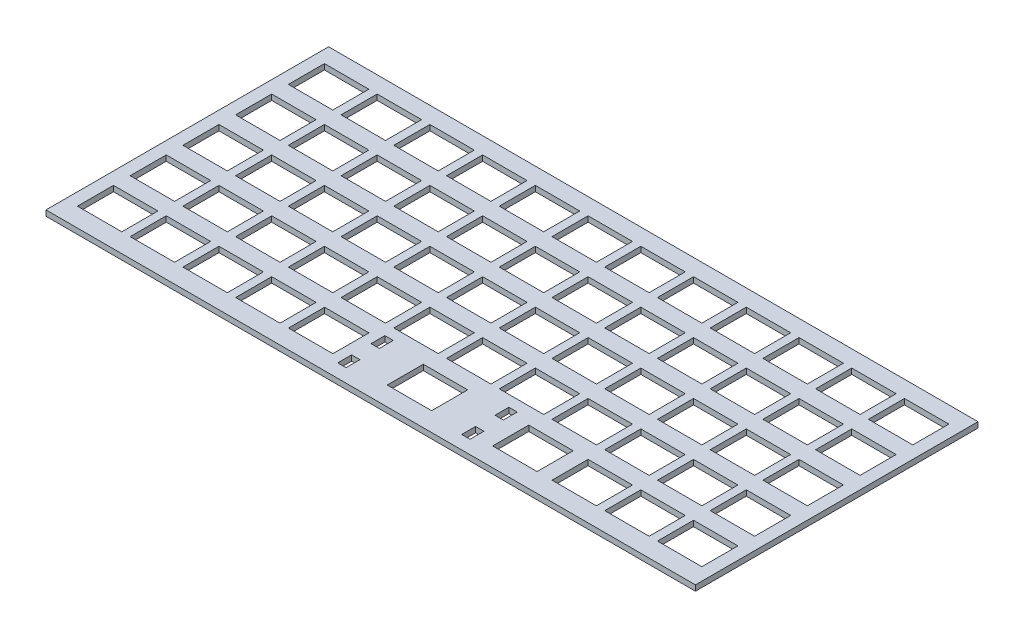
SolidWorks part; units mm, degrees
material "6061-T6 (SS)"
ref_plane "Front Plane" through (0, 0, 0) normal (0, 0, 1) x (1, 0, 0)
ref_plane "Top Plane" through (0, 0, 0) normal (0, 1, 0) x (1, 0, 0)
ref_plane "Right Plane" through (0, 0, 0) normal (1, 0, 0) x (0, 0, -1)
sketch "Sketch1" plane through (0, 0, 0) normal (0, 1, 0) x (1, 0, 0)
  line L0 (-77.1086, 41.2457) -> (-96.1086, 41.2457) construction
  line L1 (-96.1086, 41.2457) -> (-115.1086, 41.2457) construction
  line L2 (-115.1086, -53.7543) -> (-96.1086, -53.7543) construction
  line L3 (-96.1086, -53.7543) -> (-77.1086, -53.7543) construction
  line L4 (-96.1086, 22.2457) -> (-96.1086, 3.2457) construction
  line L5 (-96.1086, -15.7543) -> (-96.1086, -34.7543) construction
  line L6 (93.8914, 41.2457) -> (112.8914, 41.2457) construction
  line L7 (-115.1086, 41.2457) -> (-115.1086, 22.2457) construction
  line L8 (-77.1086, -53.7543) -> (-58.1086, -53.7543) construction
  line L9 (-58.1086, -53.7543) -> (-39.1086, -53.7543) construction
  line L10 (112.8914, 22.2457) -> (112.8914, 3.2457) construction
  line L11 (112.8914, 22.2457) -> (93.8914, 22.2457) construction
  line L12 (-77.1086, -15.7543) -> (-77.1086, 3.2457) construction
  line L13 (93.8914, 22.2457) -> (74.8914, 22.2457) construction
  line L14 (93.8914, -15.7543) -> (93.8914, 3.2457) construction
  line L15 (74.8914, 22.2457) -> (55.8914, 22.2457) construction
  line L16 (-96.1086, 22.2457) -> (-96.1086, 41.2457) construction
  line L17 (-96.1086, 22.2457) -> (-115.1086, 22.2457) construction
  line L18 (112.8914, 22.2457) -> (112.8914, 41.2457) construction
  line L19 (-39.1086, -53.7543) -> (-20.1086, -53.7543) construction
  line L20 (-20.1086, -53.7543) -> (-1.1086, -53.7543) construction
  line L21 (-77.1086, -15.7543) -> (-77.1086, -34.7543) construction
  line L22 (-77.1086, 3.2457) -> (-77.1086, 22.2457) construction
  line L23 (-77.1086, 3.2457) -> (-96.1086, 3.2457) construction
  line L24 (-96.1086, 3.2457) -> (-115.1086, 3.2457) construction
  line L25 (-77.1086, 22.2457) -> (-77.1086, 41.2457) construction
  line L26 (93.8914, 3.2457) -> (93.8914, 22.2457) construction
  line L27 (93.8914, 22.2457) -> (93.8914, 41.2457) construction
  line L28 (-77.1086, -15.7543) -> (-96.1086, -15.7543) construction
  line L29 (-96.1086, -15.7543) -> (-115.1086, -15.7543) construction
  line L30 (93.8914, 3.2457) -> (112.8914, 3.2457) construction
  line L31 (-1.1086, -53.7543) -> (17.8914, -53.7543) construction
  line L32 (-96.1086, -34.7543) -> (-115.1086, -34.7543) construction
  line L33 (-96.1086, -34.7543) -> (-96.1086, -53.7543) construction
  line L34 (-77.1086, -34.7543) -> (-77.1086, -53.7543) construction
  line L35 (93.8914, -15.7543) -> (93.8914, -34.7543) construction
  line L36 (93.8914, -34.7543) -> (93.8914, -53.7543) construction
  line L37 (93.8914, -15.7543) -> (112.8914, -15.7543) construction
  line L38 (17.8914, -53.7543) -> (36.8914, -53.7543) construction
  line L39 (112.8914, -34.7543) -> (112.8914, -53.7543) construction
  line L40 (-77.1086, 41.2457) -> (-58.1086, 41.2457) construction
  line L41 (-58.1086, 41.2457) -> (-58.1086, 22.2457) construction
  line L42 (-58.1086, 41.2457) -> (-39.1086, 41.2457) construction
  line L43 (-39.1086, 41.2457) -> (-20.1086, 41.2457) construction
  line L44 (-20.1086, 41.2457) -> (-1.1086, 41.2457) construction
  line L45 (-1.1086, 41.2457) -> (17.8914, 41.2457) construction
  line L46 (17.8914, 41.2457) -> (36.8914, 41.2457) construction
  line L47 (-39.1086, 41.2457) -> (-39.1086, 22.2457) construction
  line L48 (-39.1086, 22.2457) -> (-39.1086, 3.2457) construction
  line L49 (-39.1086, -15.7543) -> (-39.1086, 3.2457) construction
  line L50 (-39.1086, -15.7543) -> (-39.1086, -34.7543) construction
  line L51 (-39.1086, -34.7543) -> (-39.1086, -53.7543) construction
  line L52 (36.8914, 41.2457) -> (55.8914, 41.2457) construction
  line L53 (55.8914, 41.2457) -> (74.8914, 41.2457) construction
  line L54 (93.8914, 41.2457) -> (74.8914, 41.2457) construction
  line L55 (-20.1086, -53.7543) -> (-20.1086, -34.7543) construction
  line L56 (-20.1086, -15.7543) -> (-20.1086, -34.7543) construction
  line L57 (-115.1086, 3.2457) -> (-115.1086, 22.2457) construction
  line L58 (-115.1086, -53.7543) -> (-115.1086, -34.7543) construction
  line L59 (-115.1086, -34.7543) -> (-115.1086, -15.7543) construction
  line L60 (-96.1086, -15.7543) -> (-96.1086, 3.2457) construction
  line L61 (-115.1086, -15.7543) -> (-115.1086, 3.2457) construction
  line L62 (-115.1086, -53.7543) -> (-96.1086, -34.7543) construction
  line L63 (36.8914, -53.7543) -> (55.8914, -53.7543) construction
  line L64 (55.8914, -53.7543) -> (74.8914, -53.7543) construction
  line L65 (74.8914, -53.7543) -> (93.8914, -53.7543) construction
  line L66 (93.8914, -53.7543) -> (112.8914, -53.7543) construction
  line L67 (112.8914, 3.2457) -> (112.8914, -15.7543) construction
  line L68 (112.8914, -15.7543) -> (112.8914, -34.7543) construction
  line L69 (-58.1086, 22.2457) -> (-58.1086, 3.2457) construction
  line L70 (-58.1086, 3.2457) -> (-58.1086, -15.7543) construction
  line L71 (55.8914, 22.2457) -> (36.8914, 22.2457) construction
  line L72 (36.8914, 22.2457) -> (17.8914, 22.2457) construction
  line L73 (17.8914, 22.2457) -> (-1.1086, 22.2457) construction
  line L74 (-1.1086, 22.2457) -> (-20.1086, 22.2457) construction
  line L75 (-20.1086, 22.2457) -> (-39.1086, 22.2457) construction
  line L76 (-39.1086, 22.2457) -> (-58.1086, 22.2457) construction
  line L77 (-58.1086, 22.2457) -> (-77.1086, 22.2457) construction
  line L78 (-77.1086, 22.2457) -> (-96.1086, 22.2457) construction
  line L79 (-96.1086, -34.7543) -> (-77.1086, -34.7543) construction
  line L80 (-77.1086, -34.7543) -> (-58.1086, -34.7543) construction
  line L81 (-58.1086, -34.7543) -> (-39.1086, -34.7543) construction
  line L82 (-39.1086, -34.7543) -> (-20.1086, -34.7543) construction
  line L83 (-20.1086, -34.7543) -> (-1.1086, -34.7543) construction
  line L84 (-1.1086, -34.7543) -> (17.8914, -34.7543) construction
  line L85 (17.8914, -34.7543) -> (36.8914, -34.7543) construction
  line L86 (36.8914, -34.7543) -> (55.8914, -34.7543) construction
  line L87 (55.8914, -34.7543) -> (74.8914, -34.7543) construction
  line L88 (74.8914, -34.7543) -> (93.8914, -34.7543) construction
  line L89 (93.8914, -15.7543) -> (74.8914, -15.7543) construction
  line L90 (74.8914, -15.7543) -> (55.8914, -15.7543) construction
  line L91 (55.8914, -15.7543) -> (36.8914, -15.7543) construction
  line L92 (36.8914, -15.7543) -> (17.8914, -15.7543) construction
  line L93 (17.8914, -15.7543) -> (-1.1086, -15.7543) construction
  line L94 (-1.1086, -15.7543) -> (-20.1086, -15.7543) construction
  line L95 (-20.1086, -15.7543) -> (-39.1086, -15.7543) construction
  line L96 (-39.1086, -15.7543) -> (-58.1086, -15.7543) construction
  line L97 (-58.1086, -15.7543) -> (-77.1086, -15.7543) construction
  line L98 (-77.1086, 3.2457) -> (-58.1086, 3.2457) construction
  line L99 (-58.1086, 3.2457) -> (-39.1086, 3.2457) construction
  line L100 (-39.1086, 3.2457) -> (-20.1086, 3.2457) construction
  line L101 (-20.1086, 3.2457) -> (-1.1086, 3.2457) construction
  line L102 (-1.1086, 3.2457) -> (17.8914, 3.2457) construction
  line L103 (17.8914, 3.2457) -> (36.8914, 3.2457) construction
  line L104 (36.8914, 3.2457) -> (55.8914, 3.2457) construction
  line L105 (55.8914, 3.2457) -> (74.8914, 3.2457) construction
  line L106 (74.8914, 3.2457) -> (93.8914, 3.2457) construction
  line L107 (112.8914, -34.7543) -> (93.8914, -34.7543) construction
  line L108 (-20.1086, 22.2457) -> (-20.1086, 41.2457) construction
  line L109 (-1.1086, 41.2457) -> (-1.1086, 22.2457) construction
  line L110 (-1.1086, 3.2457) -> (-1.1086, 22.2457) construction
  line L111 (-58.1086, -15.7543) -> (-58.1086, -34.7543) construction
  line L112 (-20.1086, 22.2457) -> (-20.1086, 3.2457) construction
  line L113 (-58.1086, -53.7543) -> (-58.1086, -34.7543) construction
  line L114 (-20.1086, 3.2457) -> (-20.1086, -15.7543) construction
  line L115 (-1.1086, -15.7543) -> (-1.1086, 3.2457) construction
  line L116 (-1.1086, -15.7543) -> (-1.1086, -34.7543) construction
  line L117 (-1.1086, -53.7543) -> (-1.1086, -34.7543) construction
  line L118 (17.8914, -34.7543) -> (17.8914, -15.7543) construction
  line L119 (36.8914, -34.7543) -> (36.8914, -15.7543) construction
  line L120 (55.8914, -34.7543) -> (55.8914, -15.7543) construction
  line L121 (74.8914, -34.7543) -> (74.8914, -15.7543) construction
  line L122 (74.8914, -53.7543) -> (74.8914, -34.7543) construction
  line L123 (55.8914, -53.7543) -> (55.8914, -34.7543) construction
  line L124 (36.8914, -34.7543) -> (36.8914, -53.7543) construction
  line L125 (-17.8209, -31.7543) -> (-17.8209, -35.7543) construction
  line L126 (17.8914, -53.7543) -> (17.8914, -34.7543) construction
  line L127 (17.8914, 3.2457) -> (17.8914, 22.2457) construction
  line L128 (17.8914, 41.2457) -> (17.8914, 22.2457) construction
  line L129 (36.8914, 41.2457) -> (36.8914, 22.2457) construction
  line L130 (55.8914, 41.2457) -> (55.8914, 22.2457) construction
  line L131 (74.8914, 41.2457) -> (74.8914, 22.2457) construction
  line L132 (74.8914, 3.2457) -> (74.8914, 22.2457) construction
  line L133 (74.8914, -15.7543) -> (74.8914, 3.2457) construction
  line L134 (55.8914, 3.2457) -> (55.8914, 22.2457) construction
  line L135 (36.8914, 22.2457) -> (36.8914, 3.2457) construction
  line L136 (36.8914, -15.7543) -> (36.8914, 3.2457) construction
  line L137 (-20.1086, -35.7543) -> (32.1414, -35.7543) construction
  line L138 (55.8914, 3.2457) -> (55.8914, -15.7543) construction
  line L139 (17.8914, -15.7543) -> (17.8914, 3.2457) construction
  line L140 (-115.1086, 41.2457) -> (-115.1086, 44.2457) construction
  line L141 (112.8914, -53.7543) -> (115.8914, -53.7543) construction
  line L142 (-118.1086, 44.2457) -> (115.8914, 44.2457)
  line L143 (115.8914, 44.2457) -> (115.8914, -57.5769)
  line L144 (115.8914, -57.5769) -> (-118.1086, -57.5769)
  line L145 (-118.1086, -57.5769) -> (-118.1086, 44.2457)
  line L146 (-96.1086, -34.7543) -> (-115.1086, -15.7543) construction
  line L147 (-115.1086, -15.7543) -> (-96.1086, 3.2457) construction
  line L148 (-96.1086, 3.2457) -> (-115.1086, 22.2457) construction
  line L149 (-115.1086, 22.2457) -> (-96.1086, 41.2457) construction
  line L150 (-96.1086, 22.2457) -> (-77.1086, 41.2457) construction
  line L151 (-96.1086, 22.2457) -> (-77.1086, 3.2457) construction
  line L152 (-77.1086, 3.2457) -> (-96.1086, -15.7543) construction
  line L153 (-96.1086, -15.7543) -> (-77.1086, -34.7543) construction
  line L154 (-77.1086, -34.7543) -> (-96.1086, -53.7543) construction
  line L155 (-77.1086, -53.7543) -> (-58.1086, -34.7543) construction
  line L156 (-58.1086, -34.7543) -> (-77.1086, -15.7543) construction
  line L157 (-77.1086, -15.7543) -> (-58.1086, 3.2457) construction
  line L158 (-58.1086, 3.2457) -> (-77.1086, 22.2457) construction
  line L159 (-77.1086, 22.2457) -> (-58.1086, 41.2457) construction
  line L160 (-58.1086, -53.7543) -> (-39.1086, -34.7543) construction
  line L161 (-39.1086, -34.7543) -> (-58.1086, -15.7543) construction
  line L162 (-58.1086, -15.7543) -> (-39.1086, 3.2457) construction
  line L163 (-39.1086, 3.2457) -> (-58.1086, 22.2457) construction
  line L164 (-58.1086, 22.2457) -> (-39.1086, 41.2457) construction
  line L165 (93.8914, -53.7543) -> (112.8914, -34.7543) construction
  line L166 (112.8914, -34.7543) -> (93.8914, -15.7543) construction
  line L167 (93.8914, -15.7543) -> (112.8914, 3.2457) construction
  line L168 (112.8914, 3.2457) -> (93.8914, 22.2457) construction
  line L169 (93.8914, 22.2457) -> (112.8914, 41.2457) construction
  line L170 (93.8914, 41.2457) -> (74.8914, 22.2457) construction
  line L171 (74.8914, 22.2457) -> (93.8914, 3.2457) construction
  line L172 (93.8914, 3.2457) -> (74.8914, -15.7543) construction
  line L173 (74.8914, -15.7543) -> (93.8914, -34.7543) construction
  line L174 (93.8914, -34.7543) -> (74.8914, -53.7543) construction
  line L175 (55.8914, -53.7543) -> (74.8914, -34.7543) construction
  line L176 (74.8914, -34.7543) -> (55.8914, -15.7543) construction
  line L177 (55.8914, -15.7543) -> (74.8914, 3.2457) construction
  line L178 (74.8914, 3.2457) -> (55.8914, 22.2457) construction
  line L179 (55.8914, 22.2457) -> (74.8914, 41.2457) construction
  line L180 (55.8914, 41.2457) -> (36.8914, 22.2457) construction
  line L181 (36.8914, 22.2457) -> (55.8914, 3.2457) construction
  line L182 (55.8914, 3.2457) -> (36.8914, -15.7543) construction
  line L183 (36.8914, -15.7543) -> (55.8914, -34.7543) construction
  line L184 (-14.8209, -40.7543) -> (-1.9836, -40.7543) construction
  line L185 (36.8914, -34.7543) -> (17.8914, -15.7543) construction
  line L186 (-1.1086, -34.7543) -> (-20.1086, -15.7543) construction
  line L187 (-20.1086, -15.7543) -> (-1.1086, 3.2457) construction
  line L188 (-1.1086, 3.2457) -> (-20.1086, 22.2457) construction
  line L189 (-20.1086, 22.2457) -> (-1.1086, 41.2457) construction
  line L190 (14.0164, -40.7543) -> (26.8537, -40.7543) construction
  line L191 (17.8914, -34.7543) -> (-1.1086, -15.7543) construction
  line L192 (-1.1086, -15.7543) -> (17.8914, 3.2457) construction
  line L193 (17.8914, 3.2457) -> (-1.1086, 22.2457) construction
  line L194 (-1.1086, 22.2457) -> (17.8914, 41.2457) construction
  line L195 (36.8914, 41.2457) -> (17.8914, 22.2457) construction
  line L196 (17.8914, 22.2457) -> (36.8914, 3.2457) construction
  line L197 (36.8914, 3.2457) -> (17.8914, -15.7543) construction
  line L198 (-39.1086, -53.7543) -> (-20.1086, -34.7543) construction
  line L199 (-20.1086, -34.7543) -> (-39.1086, -15.7543) construction
  line L200 (-39.1086, -15.7543) -> (-20.1086, 3.2457) construction
  line L201 (-20.1086, 3.2457) -> (-39.1086, 22.2457) construction
  line L202 (-39.1086, 22.2457) -> (-20.1086, 41.2457) construction
  line L203 (-14.8209, -35.7543) -> (-17.8209, -35.7543)
  line L204 (-97.6086, 25.2457) -> (-113.6086, 25.2457)
  line L205 (-97.6086, 25.2457) -> (-97.6086, 38.2457)
  line L206 (-97.6086, 38.2457) -> (-113.6086, 38.2457)
  line L207 (-113.6086, 25.2457) -> (-113.6086, 38.2457)
  line L208 (-97.6086, 25.2457) -> (-113.6086, 38.2457) construction
  line L209 (-97.6086, 38.2457) -> (-113.6086, 25.2457) construction
  line L210 (-78.6086, 25.2457) -> (-94.6086, 25.2457)
  line L211 (-78.6086, 25.2457) -> (-78.6086, 38.2457)
  line L212 (-78.6086, 38.2457) -> (-94.6086, 38.2457)
  line L213 (-94.6086, 25.2457) -> (-94.6086, 38.2457)
  line L214 (-78.6086, 25.2457) -> (-94.6086, 38.2457) construction
  line L215 (-78.6086, 38.2457) -> (-94.6086, 25.2457) construction
  line L216 (-59.6086, 25.2457) -> (-75.6086, 25.2457)
  line L217 (-59.6086, 25.2457) -> (-59.6086, 38.2457)
  line L218 (-59.6086, 38.2457) -> (-75.6086, 38.2457)
  line L219 (-75.6086, 25.2457) -> (-75.6086, 38.2457)
  line L220 (-59.6086, 25.2457) -> (-75.6086, 38.2457) construction
  line L221 (-59.6086, 38.2457) -> (-75.6086, 25.2457) construction
  line L222 (-97.6086, 6.2457) -> (-113.6086, 6.2457)
  line L223 (-97.6086, 6.2457) -> (-97.6086, 19.2457)
  line L224 (-97.6086, 19.2457) -> (-113.6086, 19.2457)
  line L225 (-113.6086, 6.2457) -> (-113.6086, 19.2457)
  line L226 (-97.6086, 6.2457) -> (-113.6086, 19.2457) construction
  line L227 (-97.6086, 19.2457) -> (-113.6086, 6.2457) construction
  line L228 (-78.6086, 6.2457) -> (-94.6086, 6.2457)
  line L229 (-78.6086, 6.2457) -> (-78.6086, 19.2457)
  line L230 (-78.6086, 19.2457) -> (-94.6086, 19.2457)
  line L231 (-94.6086, 6.2457) -> (-94.6086, 19.2457)
  line L232 (-78.6086, 6.2457) -> (-94.6086, 19.2457) construction
  line L233 (-78.6086, 19.2457) -> (-94.6086, 6.2457) construction
  line L234 (-59.6086, 6.2457) -> (-75.6086, 6.2457)
  line L235 (-59.6086, 6.2457) -> (-59.6086, 19.2457)
  line L236 (-59.6086, 19.2457) -> (-75.6086, 19.2457)
  line L237 (-75.6086, 6.2457) -> (-75.6086, 19.2457)
  line L238 (-59.6086, 6.2457) -> (-75.6086, 19.2457) construction
  line L239 (-59.6086, 19.2457) -> (-75.6086, 6.2457) construction
  line L240 (-78.6086, -12.7543) -> (-94.6086, -12.7543)
  line L241 (-78.6086, -12.7543) -> (-78.6086, 0.2457)
  line L242 (-78.6086, 0.2457) -> (-94.6086, 0.2457)
  line L243 (-94.6086, -12.7543) -> (-94.6086, 0.2457)
  line L244 (-78.6086, -12.7543) -> (-94.6086, 0.2457) construction
  line L245 (-78.6086, 0.2457) -> (-94.6086, -12.7543) construction
  line L246 (-113.6086, -12.7543) -> (-97.6086, -12.7543)
  line L247 (-113.6086, -12.7543) -> (-113.6086, 0.2457)
  line L248 (-113.6086, 0.2457) -> (-97.6086, 0.2457)
  line L249 (-97.6086, -12.7543) -> (-97.6086, 0.2457)
  line L250 (-113.6086, -12.7543) -> (-97.6086, 0.2457) construction
  line L251 (-113.6086, 0.2457) -> (-97.6086, -12.7543) construction
  line L252 (-59.6086, -12.7543) -> (-75.6086, -12.7543)
  line L253 (-59.6086, -12.7543) -> (-59.6086, 0.2457)
  line L254 (-59.6086, 0.2457) -> (-75.6086, 0.2457)
  line L255 (-75.6086, -12.7543) -> (-75.6086, 0.2457)
  line L256 (-59.6086, -12.7543) -> (-75.6086, 0.2457) construction
  line L257 (-59.6086, 0.2457) -> (-75.6086, -12.7543) construction
  line L258 (-40.6086, -12.7543) -> (-56.6086, -12.7543)
  line L259 (-40.6086, -12.7543) -> (-40.6086, 0.2457)
  line L260 (-40.6086, 0.2457) -> (-56.6086, 0.2457)
  line L261 (-56.6086, -12.7543) -> (-56.6086, 0.2457)
  line L262 (-40.6086, -12.7543) -> (-56.6086, 0.2457) construction
  line L263 (-40.6086, 0.2457) -> (-56.6086, -12.7543) construction
  line L264 (-40.6086, 25.2457) -> (-56.6086, 25.2457)
  line L265 (-40.6086, 25.2457) -> (-40.6086, 38.2457)
  line L266 (-40.6086, 38.2457) -> (-56.6086, 38.2457)
  line L267 (-56.6086, 25.2457) -> (-56.6086, 38.2457)
  line L268 (-40.6086, 25.2457) -> (-56.6086, 38.2457) construction
  line L269 (-40.6086, 38.2457) -> (-56.6086, 25.2457) construction
  line L270 (-40.6086, 6.2457) -> (-56.6086, 6.2457)
  line L271 (-40.6086, 6.2457) -> (-40.6086, 19.2457)
  line L272 (-40.6086, 19.2457) -> (-56.6086, 19.2457)
  line L273 (-56.6086, 6.2457) -> (-56.6086, 19.2457)
  line L274 (-40.6086, 6.2457) -> (-56.6086, 19.2457) construction
  line L275 (-40.6086, 19.2457) -> (-56.6086, 6.2457) construction
  line L276 (-113.6086, -31.7543) -> (-97.6086, -31.7543)
  line L277 (-113.6086, -31.7543) -> (-113.6086, -18.7543)
  line L278 (-113.6086, -18.7543) -> (-97.6086, -18.7543)
  line L279 (-97.6086, -31.7543) -> (-97.6086, -18.7543)
  line L280 (-113.6086, -31.7543) -> (-97.6086, -18.7543) construction
  line L281 (-113.6086, -18.7543) -> (-97.6086, -31.7543) construction
  line L282 (-78.6086, -31.7543) -> (-94.6086, -31.7543)
  line L283 (-78.6086, -31.7543) -> (-78.6086, -18.7543)
  line L284 (-78.6086, -18.7543) -> (-94.6086, -18.7543)
  line L285 (-94.6086, -31.7543) -> (-94.6086, -18.7543)
  line L286 (-78.6086, -31.7543) -> (-94.6086, -18.7543) construction
  line L287 (-78.6086, -18.7543) -> (-94.6086, -31.7543) construction
  line L288 (-59.6086, -31.7543) -> (-75.6086, -31.7543)
  line L289 (-59.6086, -31.7543) -> (-59.6086, -18.7543)
  line L290 (-59.6086, -18.7543) -> (-75.6086, -18.7543)
  line L291 (-75.6086, -31.7543) -> (-75.6086, -18.7543)
  line L292 (-59.6086, -31.7543) -> (-75.6086, -18.7543) construction
  line L293 (-59.6086, -18.7543) -> (-75.6086, -31.7543) construction
  line L294 (-40.6086, -31.7543) -> (-56.6086, -31.7543)
  line L295 (-40.6086, -31.7543) -> (-40.6086, -18.7543)
  line L296 (-40.6086, -18.7543) -> (-56.6086, -18.7543)
  line L297 (-56.6086, -31.7543) -> (-56.6086, -18.7543)
  line L298 (-40.6086, -31.7543) -> (-56.6086, -18.7543) construction
  line L299 (-40.6086, -18.7543) -> (-56.6086, -31.7543) construction
  line L300 (-97.6086, -50.7543) -> (-113.6086, -50.7543)
  line L301 (-97.6086, -50.7543) -> (-97.6086, -37.7543)
  line L302 (-97.6086, -37.7543) -> (-113.6086, -37.7543)
  line L303 (-113.6086, -50.7543) -> (-113.6086, -37.7543)
  line L304 (-97.6086, -50.7543) -> (-113.6086, -37.7543) construction
  line L305 (-97.6086, -37.7543) -> (-113.6086, -50.7543) construction
  line L306 (-78.6086, -50.7543) -> (-94.6086, -50.7543)
  line L307 (-78.6086, -50.7543) -> (-78.6086, -37.7543)
  line L308 (-78.6086, -37.7543) -> (-94.6086, -37.7543)
  line L309 (-94.6086, -50.7543) -> (-94.6086, -37.7543)
  line L310 (-78.6086, -50.7543) -> (-94.6086, -37.7543) construction
  line L311 (-78.6086, -37.7543) -> (-94.6086, -50.7543) construction
  line L312 (-59.6086, -50.7543) -> (-75.6086, -50.7543)
  line L313 (-59.6086, -50.7543) -> (-59.6086, -37.7543)
  line L314 (-59.6086, -37.7543) -> (-75.6086, -37.7543)
  line L315 (-75.6086, -50.7543) -> (-75.6086, -37.7543)
  line L316 (-59.6086, -50.7543) -> (-75.6086, -37.7543) construction
  line L317 (-59.6086, -37.7543) -> (-75.6086, -50.7543) construction
  line L318 (-40.6086, -50.7543) -> (-56.6086, -50.7543)
  line L319 (-40.6086, -50.7543) -> (-40.6086, -37.7543)
  line L320 (-40.6086, -37.7543) -> (-56.6086, -37.7543)
  line L321 (-56.6086, -50.7543) -> (-56.6086, -37.7543)
  line L322 (-40.6086, -50.7543) -> (-56.6086, -37.7543) construction
  line L323 (-40.6086, -37.7543) -> (-56.6086, -50.7543) construction
  line L324 (95.3914, -37.7543) -> (111.3914, -37.7543)
  line L325 (95.3914, -37.7543) -> (95.3914, -50.7543)
  line L326 (95.3914, -50.7543) -> (111.3914, -50.7543)
  line L327 (111.3914, -37.7543) -> (111.3914, -50.7543)
  line L328 (95.3914, -37.7543) -> (111.3914, -50.7543) construction
  line L329 (95.3914, -50.7543) -> (111.3914, -37.7543) construction
  line L330 (92.3914, -31.7543) -> (76.3914, -31.7543)
  line L331 (92.3914, -31.7543) -> (92.3914, -18.7543)
  line L332 (92.3914, -18.7543) -> (76.3914, -18.7543)
  line L333 (76.3914, -31.7543) -> (76.3914, -18.7543)
  line L334 (92.3914, -31.7543) -> (76.3914, -18.7543) construction
  line L335 (92.3914, -18.7543) -> (76.3914, -31.7543) construction
  line L336 (76.3914, -50.7543) -> (92.3914, -50.7543)
  line L337 (76.3914, -50.7543) -> (76.3914, -37.7543)
  line L338 (76.3914, -37.7543) -> (92.3914, -37.7543)
  line L339 (92.3914, -50.7543) -> (92.3914, -37.7543)
  line L340 (76.3914, -50.7543) -> (92.3914, -37.7543) construction
  line L341 (76.3914, -37.7543) -> (92.3914, -50.7543) construction
  line L342 (111.3914, -18.7543) -> (95.3914, -18.7543)
  line L343 (111.3914, -18.7543) -> (111.3914, -31.7543)
  line L344 (111.3914, -31.7543) -> (95.3914, -31.7543)
  line L345 (95.3914, -18.7543) -> (95.3914, -31.7543)
  line L346 (111.3914, -18.7543) -> (95.3914, -31.7543) construction
  line L347 (111.3914, -31.7543) -> (95.3914, -18.7543) construction
  line L348 (57.3914, 0.2457) -> (73.3914, 0.2457)
  line L349 (57.3914, 0.2457) -> (57.3914, -12.7543)
  line L350 (57.3914, -12.7543) -> (73.3914, -12.7543)
  line L351 (73.3914, 0.2457) -> (73.3914, -12.7543)
  line L352 (57.3914, 0.2457) -> (73.3914, -12.7543) construction
  line L353 (57.3914, -12.7543) -> (73.3914, 0.2457) construction
  line L354 (57.3914, -31.7543) -> (73.3914, -31.7543)
  line L355 (57.3914, -31.7543) -> (57.3914, -18.7543)
  line L356 (57.3914, -18.7543) -> (73.3914, -18.7543)
  line L357 (73.3914, -31.7543) -> (73.3914, -18.7543)
  line L358 (57.3914, -31.7543) -> (73.3914, -18.7543) construction
  line L359 (57.3914, -18.7543) -> (73.3914, -31.7543) construction
  line L360 (57.3914, -50.7543) -> (73.3914, -50.7543)
  line L361 (57.3914, -50.7543) -> (57.3914, -37.7543)
  line L362 (57.3914, -37.7543) -> (73.3914, -37.7543)
  line L363 (73.3914, -50.7543) -> (73.3914, -37.7543)
  line L364 (57.3914, -50.7543) -> (73.3914, -37.7543) construction
  line L365 (57.3914, -37.7543) -> (73.3914, -50.7543) construction
  line L366 (92.3914, 0.2457) -> (76.3914, 0.2457)
  line L367 (92.3914, 0.2457) -> (92.3914, -12.7543)
  line L368 (92.3914, -12.7543) -> (76.3914, -12.7543)
  line L369 (76.3914, 0.2457) -> (76.3914, -12.7543)
  line L370 (92.3914, 0.2457) -> (76.3914, -12.7543) construction
  line L371 (92.3914, -12.7543) -> (76.3914, 0.2457) construction
  line L372 (111.3914, 0.2457) -> (95.3914, 0.2457)
  line L373 (111.3914, 0.2457) -> (111.3914, -12.7543)
  line L374 (111.3914, -12.7543) -> (95.3914, -12.7543)
  line L375 (95.3914, 0.2457) -> (95.3914, -12.7543)
  line L376 (111.3914, 0.2457) -> (95.3914, -12.7543) construction
  line L377 (111.3914, -12.7543) -> (95.3914, 0.2457) construction
  line L378 (-21.557, -50.7543) -> (-37.557, -50.7543)
  line L379 (-21.557, -50.7543) -> (-21.557, -37.7543)
  line L380 (-21.557, -37.7543) -> (-37.557, -37.7543)
  line L381 (-37.557, -50.7543) -> (-37.557, -37.7543)
  line L382 (-21.557, -50.7543) -> (-37.557, -37.7543) construction
  line L383 (-21.557, -37.7543) -> (-37.557, -50.7543) construction
  line L384 (-21.6086, -18.7543) -> (-37.6086, -18.7543)
  line L385 (-21.6086, -18.7543) -> (-21.6086, -31.7543)
  line L386 (-21.6086, -31.7543) -> (-37.6086, -31.7543)
  line L387 (-37.6086, -18.7543) -> (-37.6086, -31.7543)
  line L388 (-21.6086, -18.7543) -> (-37.6086, -31.7543) construction
  line L389 (-21.6086, -31.7543) -> (-37.6086, -18.7543) construction
  line L390 (-21.6086, 0.2457) -> (-37.6086, 0.2457)
  line L391 (-21.6086, 0.2457) -> (-21.6086, -12.7543)
  line L392 (-21.6086, -12.7543) -> (-37.6086, -12.7543)
  line L393 (-37.6086, 0.2457) -> (-37.6086, -12.7543)
  line L394 (-21.6086, 0.2457) -> (-37.6086, -12.7543) construction
  line L395 (-21.6086, -12.7543) -> (-37.6086, 0.2457) construction
  line L396 (-21.6086, 19.2457) -> (-37.6086, 19.2457)
  line L397 (-21.6086, 19.2457) -> (-21.6086, 6.2457)
  line L398 (-21.6086, 6.2457) -> (-37.6086, 6.2457)
  line L399 (-37.6086, 19.2457) -> (-37.6086, 6.2457)
  line L400 (-21.6086, 19.2457) -> (-37.6086, 6.2457) construction
  line L401 (-21.6086, 6.2457) -> (-37.6086, 19.2457) construction
  line L402 (-21.6086, 38.2457) -> (-37.6086, 38.2457)
  line L403 (-21.6086, 38.2457) -> (-21.6086, 25.2457)
  line L404 (-21.6086, 25.2457) -> (-37.6086, 25.2457)
  line L405 (-37.6086, 38.2457) -> (-37.6086, 25.2457)
  line L406 (-21.6086, 38.2457) -> (-37.6086, 25.2457) construction
  line L407 (-21.6086, 25.2457) -> (-37.6086, 38.2457) construction
  line L408 (73.3914, 19.2457) -> (57.3914, 19.2457)
  line L409 (73.3914, 19.2457) -> (73.3914, 6.2457)
  line L410 (73.3914, 6.2457) -> (57.3914, 6.2457)
  line L411 (57.3914, 19.2457) -> (57.3914, 6.2457)
  line L412 (73.3914, 19.2457) -> (57.3914, 6.2457) construction
  line L413 (73.3914, 6.2457) -> (57.3914, 19.2457) construction
  line L414 (38.3914, 38.2457) -> (54.3914, 38.2457)
  line L415 (38.3914, 38.2457) -> (38.3914, 25.2457)
  line L416 (38.3914, 25.2457) -> (54.3914, 25.2457)
  line L417 (54.3914, 38.2457) -> (54.3914, 25.2457)
  line L418 (38.3914, 38.2457) -> (54.3914, 25.2457) construction
  line L419 (38.3914, 25.2457) -> (54.3914, 38.2457) construction
  line L420 (38.3914, 6.2457) -> (54.3914, 6.2457)
  line L421 (38.3914, 6.2457) -> (38.3914, 19.2457)
  line L422 (38.3914, 19.2457) -> (54.3914, 19.2457)
  line L423 (54.3914, 6.2457) -> (54.3914, 19.2457)
  line L424 (38.3914, 6.2457) -> (54.3914, 19.2457) construction
  line L425 (38.3914, 19.2457) -> (54.3914, 6.2457) construction
  line L426 (73.3914, 38.2457) -> (57.3914, 38.2457)
  line L427 (73.3914, 38.2457) -> (73.3914, 25.2457)
  line L428 (73.3914, 25.2457) -> (57.3914, 25.2457)
  line L429 (57.3914, 38.2457) -> (57.3914, 25.2457)
  line L430 (73.3914, 38.2457) -> (57.3914, 25.2457) construction
  line L431 (73.3914, 25.2457) -> (57.3914, 38.2457) construction
  line L432 (92.3914, 38.2457) -> (76.3914, 38.2457)
  line L433 (92.3914, 38.2457) -> (92.3914, 25.2457)
  line L434 (92.3914, 25.2457) -> (76.3914, 25.2457)
  line L435 (76.3914, 38.2457) -> (76.3914, 25.2457)
  line L436 (92.3914, 38.2457) -> (76.3914, 25.2457) construction
  line L437 (92.3914, 25.2457) -> (76.3914, 38.2457) construction
  line L438 (111.3914, 38.2457) -> (95.3914, 38.2457)
  line L439 (111.3914, 38.2457) -> (111.3914, 25.2457)
  line L440 (111.3914, 25.2457) -> (95.3914, 25.2457)
  line L441 (95.3914, 38.2457) -> (95.3914, 25.2457)
  line L442 (111.3914, 38.2457) -> (95.3914, 25.2457) construction
  line L443 (111.3914, 25.2457) -> (95.3914, 38.2457) construction
  line L444 (92.3914, 19.2457) -> (76.3914, 19.2457)
  line L445 (92.3914, 19.2457) -> (92.3914, 6.2457)
  line L446 (92.3914, 6.2457) -> (76.3914, 6.2457)
  line L447 (76.3914, 19.2457) -> (76.3914, 6.2457)
  line L448 (92.3914, 19.2457) -> (76.3914, 6.2457) construction
  line L449 (92.3914, 6.2457) -> (76.3914, 19.2457) construction
  line L450 (111.3914, 19.2457) -> (95.3914, 19.2457)
  line L451 (111.3914, 19.2457) -> (111.3914, 6.2457)
  line L452 (111.3914, 6.2457) -> (95.3914, 6.2457)
  line L453 (95.3914, 19.2457) -> (95.3914, 6.2457)
  line L454 (111.3914, 19.2457) -> (95.3914, 6.2457) construction
  line L455 (111.3914, 6.2457) -> (95.3914, 19.2457) construction
  line L456 (38.3914, -12.7543) -> (54.3914, -12.7543)
  line L457 (38.3914, -12.7543) -> (38.3914, 0.2457)
  line L458 (38.3914, 0.2457) -> (54.3914, 0.2457)
  line L459 (54.3914, -12.7543) -> (54.3914, 0.2457)
  line L460 (38.3914, -12.7543) -> (54.3914, 0.2457) construction
  line L461 (38.3914, 0.2457) -> (54.3914, -12.7543) construction
  line L462 (38.3914, -31.7543) -> (54.3914, -31.7543)
  line L463 (38.3914, -31.7543) -> (38.3914, -18.7543)
  line L464 (38.3914, -18.7543) -> (54.3914, -18.7543)
  line L465 (54.3914, -31.7543) -> (54.3914, -18.7543)
  line L466 (38.3914, -31.7543) -> (54.3914, -18.7543) construction
  line L467 (38.3914, -18.7543) -> (54.3914, -31.7543) construction
  line L468 (19.3914, -12.7543) -> (35.3914, -12.7543)
  line L469 (19.3914, -12.7543) -> (19.3914, 0.2457)
  line L470 (19.3914, 0.2457) -> (35.3914, 0.2457)
  line L471 (35.3914, -12.7543) -> (35.3914, 0.2457)
  line L472 (19.3914, -12.7543) -> (35.3914, 0.2457) construction
  line L473 (19.3914, 0.2457) -> (35.3914, -12.7543) construction
  line L474 (19.3914, -31.7543) -> (35.3914, -31.7543)
  line L475 (19.3914, -31.7543) -> (19.3914, -18.7543)
  line L476 (19.3914, -18.7543) -> (35.3914, -18.7543)
  line L477 (35.3914, -31.7543) -> (35.3914, -18.7543)
  line L478 (19.3914, -31.7543) -> (35.3914, -18.7543) construction
  line L479 (19.3914, -18.7543) -> (35.3914, -31.7543) construction
  line L480 (19.3914, 19.2457) -> (35.3914, 19.2457)
  line L481 (19.3914, 19.2457) -> (19.3914, 6.2457)
  line L482 (19.3914, 6.2457) -> (35.3914, 6.2457)
  line L483 (35.3914, 19.2457) -> (35.3914, 6.2457)
  line L484 (19.3914, 19.2457) -> (35.3914, 6.2457) construction
  line L485 (19.3914, 6.2457) -> (35.3914, 19.2457) construction
  line L486 (19.3914, 38.2457) -> (35.3914, 38.2457)
  line L487 (19.3914, 38.2457) -> (19.3914, 25.2457)
  line L488 (19.3914, 25.2457) -> (35.3914, 25.2457)
  line L489 (35.3914, 38.2457) -> (35.3914, 25.2457)
  line L490 (19.3914, 38.2457) -> (35.3914, 25.2457) construction
  line L491 (19.3914, 25.2457) -> (35.3914, 38.2457) construction
  line L492 (0.3914, 38.2457) -> (16.3914, 38.2457)
  line L493 (0.3914, 38.2457) -> (0.3914, 25.2457)
  line L494 (0.3914, 25.2457) -> (16.3914, 25.2457)
  line L495 (16.3914, 38.2457) -> (16.3914, 25.2457)
  line L496 (0.3914, 38.2457) -> (16.3914, 25.2457) construction
  line L497 (0.3914, 25.2457) -> (16.3914, 38.2457) construction
  line L498 (-18.6086, 25.2457) -> (-2.6086, 25.2457)
  line L499 (-18.6086, 25.2457) -> (-18.6086, 38.2457)
  line L500 (-18.6086, 38.2457) -> (-2.6086, 38.2457)
  line L501 (-2.6086, 25.2457) -> (-2.6086, 38.2457)
  line L502 (-18.6086, 25.2457) -> (-2.6086, 38.2457) construction
  line L503 (-18.6086, 38.2457) -> (-2.6086, 25.2457) construction
  line L504 (-18.6086, 6.2457) -> (-2.6086, 6.2457)
  line L505 (-18.6086, 6.2457) -> (-18.6086, 19.2457)
  line L506 (-18.6086, 19.2457) -> (-2.6086, 19.2457)
  line L507 (-2.6086, 6.2457) -> (-2.6086, 19.2457)
  line L508 (-18.6086, 6.2457) -> (-2.6086, 19.2457) construction
  line L509 (-18.6086, 19.2457) -> (-2.6086, 6.2457) construction
  line L510 (0.3914, 6.2457) -> (16.3914, 6.2457)
  line L511 (0.3914, 6.2457) -> (0.3914, 19.2457)
  line L512 (0.3914, 19.2457) -> (16.3914, 19.2457)
  line L513 (16.3914, 6.2457) -> (16.3914, 19.2457)
  line L514 (0.3914, 6.2457) -> (16.3914, 19.2457) construction
  line L515 (0.3914, 19.2457) -> (16.3914, 6.2457) construction
  line L516 (0.3914, -12.7543) -> (16.3914, -12.7543)
  line L517 (0.3914, -12.7543) -> (0.3914, 0.2457)
  line L518 (0.3914, 0.2457) -> (16.3914, 0.2457)
  line L519 (16.3914, -12.7543) -> (16.3914, 0.2457)
  line L520 (0.3914, -12.7543) -> (16.3914, 0.2457) construction
  line L521 (0.3914, 0.2457) -> (16.3914, -12.7543) construction
  line L522 (-2.6086, -12.7543) -> (-18.6086, -12.7543)
  line L523 (-2.6086, -12.7543) -> (-2.6086, 0.2457)
  line L524 (-2.6086, 0.2457) -> (-18.6086, 0.2457)
  line L525 (-18.6086, -12.7543) -> (-18.6086, 0.2457)
  line L526 (-2.6086, -12.7543) -> (-18.6086, 0.2457) construction
  line L527 (-2.6086, 0.2457) -> (-18.6086, -12.7543) construction
  line L528 (-2.6086, -18.7543) -> (-18.6086, -18.7543)
  line L529 (-2.6086, -18.7543) -> (-2.6086, -31.7543)
  line L530 (-2.6086, -31.7543) -> (-18.6086, -31.7543)
  line L531 (-18.6086, -18.7543) -> (-18.6086, -31.7543)
  line L532 (-2.6086, -18.7543) -> (-18.6086, -31.7543) construction
  line L533 (-2.6086, -31.7543) -> (-18.6086, -18.7543) construction
  line L534 (16.3914, -31.7543) -> (0.3914, -31.7543)
  line L535 (16.3914, -31.7543) -> (16.3914, -18.7543)
  line L536 (16.3914, -18.7543) -> (0.3914, -18.7543)
  line L537 (0.3914, -31.7543) -> (0.3914, -18.7543)
  line L538 (16.3914, -31.7543) -> (0.3914, -18.7543) construction
  line L539 (16.3914, -18.7543) -> (0.3914, -31.7543) construction
  line L540 (-14.8209, -35.7543) -> (-14.8209, -40.7543)
  line L541 (-14.8209, -40.7543) -> (-17.8209, -40.7543)
  line L542 (32.1414, -53.7543) -> (32.1414, -34.7543) construction
  line L543 (32.1414, -53.7543) -> (55.8914, -34.7543) construction
  line L544 (32.1414, -34.7543) -> (55.8914, -53.7543) construction
  line L545 (-20.1086, -53.7543) -> (32.1414, -34.7543) construction
  line L546 (36.0164, -50.7543) -> (52.0164, -50.7543)
  line L547 (36.0164, -50.7543) -> (36.0164, -37.7543)
  line L548 (36.0164, -37.7543) -> (52.0164, -37.7543)
  line L549 (52.0164, -50.7543) -> (52.0164, -37.7543)
  line L550 (36.0164, -50.7543) -> (52.0164, -37.7543) construction
  line L551 (36.0164, -37.7543) -> (52.0164, -50.7543) construction
  line L552 (-17.8209, -35.7543) -> (-17.8209, -40.7543)
  line L553 (-20.1086, -34.7543) -> (32.1414, -53.7543) construction
  line L554 (-1.9836, -37.7543) -> (-1.9836, -40.7543) construction
  line L555 (-1.9836, -50.7543) -> (14.0164, -50.7543)
  line L556 (-1.9836, -37.7543) -> (-1.9836, -50.7543)
  line L557 (-1.9836, -37.7543) -> (14.0164, -37.7543)
  line L558 (14.0164, -40.7543) -> (14.0164, -37.7543) construction
  line L559 (-1.9836, -50.7543) -> (14.0164, -37.7543) construction
  line L560 (-1.9836, -37.7543) -> (14.0164, -50.7543) construction
  line L561 (26.8537, -40.7543) -> (29.8537, -40.7543)
  line L562 (26.8537, -40.7543) -> (26.8537, -35.7543)
  line L563 (26.8537, -35.7543) -> (29.8537, -35.7543)
  line L564 (29.8537, -40.7543) -> (29.8537, -35.7543)
  line L565 (-1.9836, -50.7543) -> (-1.9836, -47.7543) construction
  line L566 (-1.9836, -47.7543) -> (-14.8209, -47.7543) construction
  line L567 (14.0164, -50.7543) -> (14.0164, -47.7543) construction
  line L568 (-14.8209, -47.7543) -> (-17.8209, -47.7543)
  line L569 (-14.8209, -47.7543) -> (-14.8209, -52.7543)
  line L570 (-14.8209, -52.7543) -> (-17.8209, -52.7543)
  line L571 (-17.8209, -47.7543) -> (-17.8209, -52.7543)
  line L572 (14.0164, -47.7543) -> (26.8537, -47.7543) construction
  line L573 (14.0164, -37.7543) -> (14.0164, -50.7543)
  line L574 (14.0164, -50.7543) -> (14.036, -50.7177)
  line L576 (26.8537, -47.7543) -> (29.8537, -47.7543)
  line L577 (26.8537, -47.7543) -> (26.8537, -52.7543)
  line L578 (26.8537, -52.7543) -> (29.8537, -52.7543)
  line L579 (29.8537, -47.7543) -> (29.8537, -52.7543)
  point P1 (-105.6086, 31.7457)
  point P89 (-86.6086, 31.7457)
  point P94 (-67.6086, 31.7457)
  point P99 (-105.6086, 12.7457)
  point P104 (-86.6086, 12.7457)
  point P109 (-67.6086, 12.7457)
  point P114 (-86.6086, -6.2543)
  point P119 (-105.6086, -6.2543)
  point P124 (-67.6086, -6.2543)
  point P129 (-48.6086, -6.2543)
  point P134 (-48.6086, 31.7457)
  point P139 (-48.6086, 12.7457)
  point P144 (-105.6086, -25.2543)
  point P149 (-86.6086, -25.2543)
  point P154 (-67.6086, -25.2543)
  point P159 (-48.6086, -25.2543)
  point P164 (-105.6086, -44.2543)
  point P169 (-86.6086, -44.2543)
  point P174 (-67.6086, -44.2543)
  point P179 (-48.6086, -44.2543)
  point P184 (103.3914, -44.2543)
  point P189 (84.3914, -44.2543)
  point P190 (84.3914, -25.2543)
  point P199 (103.3914, -25.2543)
  point P204 (65.3914, -6.2543)
  point P209 (65.3914, -25.2543)
  point P214 (65.3914, -44.2543)
  point P219 (84.3914, -6.2543)
  point P224 (103.3914, -6.2543)
  point P229 (-29.557, -44.2543)
  point P234 (-29.6086, -25.2543)
  point P239 (-29.6086, -6.2543)
  point P244 (-29.6086, 12.7457)
  point P249 (-29.6086, 31.7457)
  point P254 (65.3914, 12.7457)
  point P259 (46.3914, 31.7457)
  point P264 (46.3914, 12.7457)
  point P269 (65.3914, 31.7457)
  point P274 (84.3914, 31.7457)
  point P279 (103.3914, 31.7457)
  point P284 (84.3914, 12.7457)
  point P289 (103.3914, 12.7457)
  point P294 (46.3914, -6.2543)
  point P299 (46.3914, -25.2543)
  point P304 (27.3914, -6.2543)
  point P309 (27.3914, -25.2543)
  point P314 (27.3914, 12.7457)
  point P319 (27.3914, 31.7457)
  point P324 (8.3914, 31.7457)
  point P329 (-10.6086, 31.7457)
  point P334 (-10.6086, 12.7457)
  point P339 (8.3914, 12.7457)
  point P344 (8.3914, -6.2543)
  point P349 (-10.6086, -6.2543)
  point P354 (-10.6086, -25.2543)
  point P359 (8.3914, -25.2543)
  point P375 (44.0164, -44.2543)
  point P380 (6.0164, -44.2543)
  dimension "D1" = 3
  dimension "D2" = 3
  dimension "D4" = 16
  dimension "D3" = 13
  dimension "D5" = 4
  dimension "D7" = 5
  dimension "D8" = 3
extrude "Boss-Extrude2" add sketch "Sketch1" along normal blind 2
